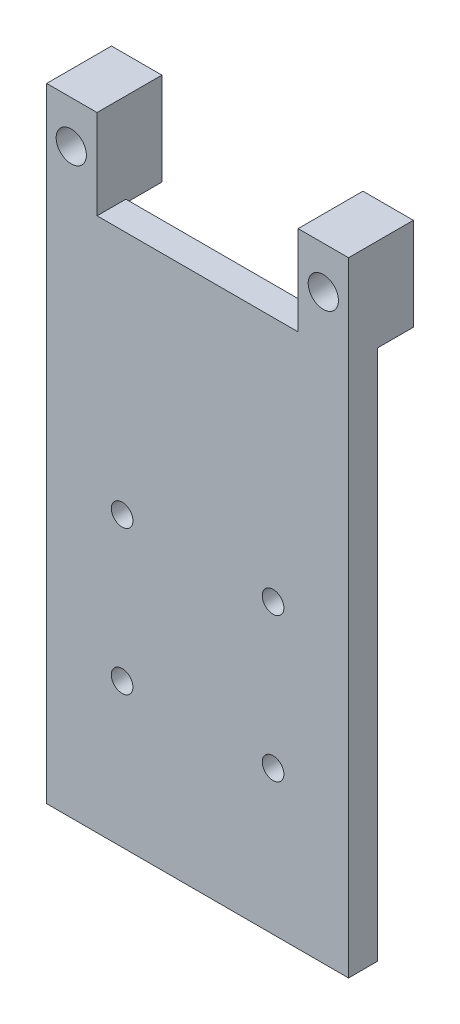
SolidWorks part; units mm, degrees
ref_plane "Alzado" through (0, 0, 0) normal (0, 0, 1) x (1, 0, 0)
ref_plane "Planta" through (0, 0, 0) normal (0, 1, 0) x (1, 0, 0)
ref_plane "Vista lateral" through (0, 0, 0) normal (1, 0, 0) x (0, 0, -1)
sketch "Croquis1" plane through (0, 0, 0) normal (0, 0, 1) x (1, 0, 0)
  line L0 (31.8089, -1059.3806) -> (31.8089, -1140.6199)
  line L1 (-10.1068, -1059.3806) -> (-10.1068, -1140.6199)
  line L2 (-10.1068, -1140.6199) -> (31.8089, -1140.6199)
  line L3 (-10.1068, -1059.3806) -> (-10.1068, -1054.0032)
  line L4 (-10.1068, -1054.0032) -> (-3.1068, -1054.0032)
  line L5 (31.8089, -1059.3806) -> (31.8089, -1054.0032)
  line L6 (31.8089, -1054.0032) -> (24.8089, -1054.0032)
  line L7 (24.8089, -1054.0032) -> (24.8089, -1066.423)
  line L8 (24.8089, -1066.423) -> (-3.1068, -1066.423)
  line L9 (-3.1068, -1066.423) -> (-3.1068, -1054.0032)
  dimension "D1" = 7
  dimension "D2" = 7
extrude "Saliente-Extruir1" add sketch "Croquis1" along normal blind 4
sketch "Croquis2" plane through (0, 0, 0) normal (0, 0, -1) x (-1, 0, 0)
  line L0 (10.1068, -1054.0032) -> (10.1068, -1140.6199) construction
  line L1 (10.1068, -1066.8699) -> (3.1068, -1066.8699)
  line L2 (10.1068, -1066.8699) -> (10.1068, -1054.0032)
  line L3 (10.1068, -1054.0032) -> (3.1068, -1054.0032)
  line L4 (3.1068, -1066.8699) -> (3.1068, -1054.0032)
  line L5 (3.1068, -1066.423) -> (3.1068, -1054.0032) construction
  line L6 (3.1068, -1054.0032) -> (10.1068, -1054.0032) construction
  line L7 (-31.8089, -1054.0032) -> (-24.8089, -1054.0032) construction
  line L8 (-31.8089, -1054.0032) -> (-24.8089, -1054.0032)
  line L9 (-31.8089, -1054.0032) -> (-31.8089, -1066.8699)
  line L10 (-31.8089, -1066.8699) -> (-24.8089, -1066.8699)
  line L11 (-24.8089, -1054.0032) -> (-24.8089, -1066.8699)
extrude "Saliente-Extruir2" add sketch "Croquis2" along normal blind 5
sketch "Croquis3" plane through (0, 0, 4) normal (0, 0, 1) x (1, 0, 0)
  circle A0 centre (-6.6911, -1059.8699) radius 2.1
  circle A1 centre (28.3089, -1059.8699) radius 2.1
extrude "Cortar-Extruir1" cut sketch "Croquis3" against normal blind 10
sketch "Croquis4" plane through (0, 0, 4) normal (0, 0, 1) x (1, 0, 0)
  line L0 (31.8089, -1140.6199) -> (-10.1068, -1140.6199) construction
  line L1 (-10.1068, -1140.6199) -> (31.8089, -1140.6199) construction
  line L2 (31.8089, -1140.6199) -> (31.8089, -1054.0032) construction
  line L3 (-10.1068, -1054.0032) -> (-10.1068, -1140.6199) construction
  line L4 (-10.1068, -1140.6199) -> (10.851, -1140.6199) construction
  line L5 (10.851, -1140.6199) -> (10.851, -1120.6199) construction
  line L6 (10.851, -1120.6199) -> (31.8089, -1120.6199) construction
  line L7 (31.8089, -1120.6199) -> (21.33, -1120.6199) construction
  line L8 (21.33, -1120.6199) -> (10.851, -1120.6199) construction
  line L9 (10.851, -1120.6199) -> (-10.1068, -1120.6199) construction
  line L10 (-10.1068, -1120.6199) -> (0.3721, -1120.6199) construction
  circle A0 centre (21.33, -1120.6199) radius 1.5
  circle A1 centre (0.3721, -1120.6199) radius 1.5
  dimension "D2" = 3
  dimension "D3" = 3
  dimension "D1" = 20
extrude "Cortar-Extruir2" cut sketch "Croquis4" against normal blind 10
sketch "Croquis5" plane through (0, 0, 4) normal (0, 0, 1) x (1, 0, 0)
  line L0 (0.3721, -1120.615) -> (0.3721, -1100.615) construction
  line L1 (0.3721, -1100.615) -> (21.33, -1120.6199) construction
  line L2 (21.33, -1120.6199) -> (21.33, -1100.6199) construction
  circle A0 centre (0.3721, -1100.615) radius 1.5
  circle A1 centre (21.33, -1100.6199) radius 1.5
  dimension "D3" = 3
  dimension "D4" = 3
  dimension "D1" = 20
  dimension "D2" = 20
extrude "Cortar-Extruir3" cut sketch "Croquis5" against normal blind 10
